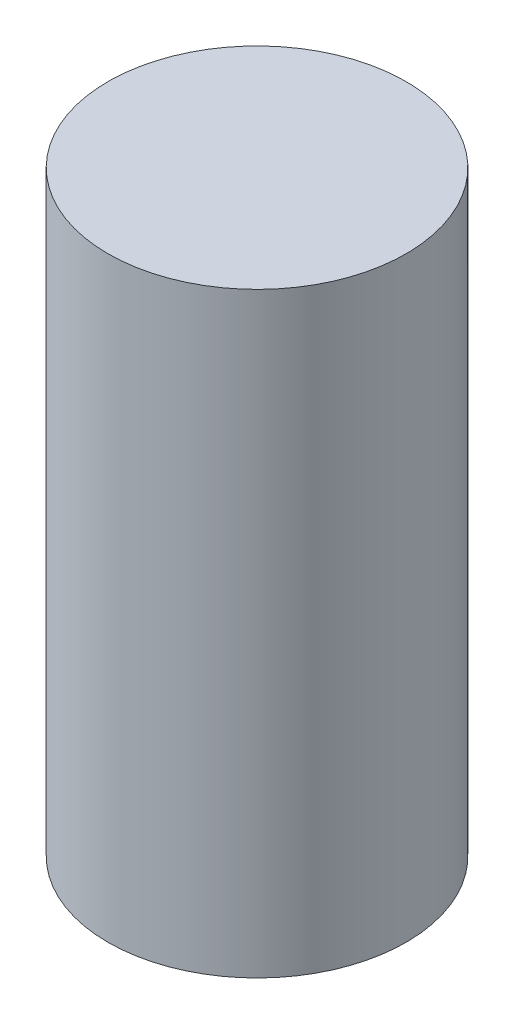
SolidWorks part; units mm, degrees
ref_plane "Front Plane" through (0, 0, 0) normal (0, 0, 1) x (1, 0, 0)
ref_plane "Top Plane" through (0, 0, 0) normal (0, 1, 0) x (1, 0, 0)
ref_plane "Right Plane" through (0, 0, 0) normal (1, 0, 0) x (0, 0, -1)
sketch "Sketch1" plane through (0, 0, 0) normal (0, 1, 0) x (1, 0, 0)
  circle A0 centre (0, 0) radius 25.4
  dimension "D1" = 50.8
extrude "Boss-Extrude1" add sketch "Sketch1" along normal blind 101.6
